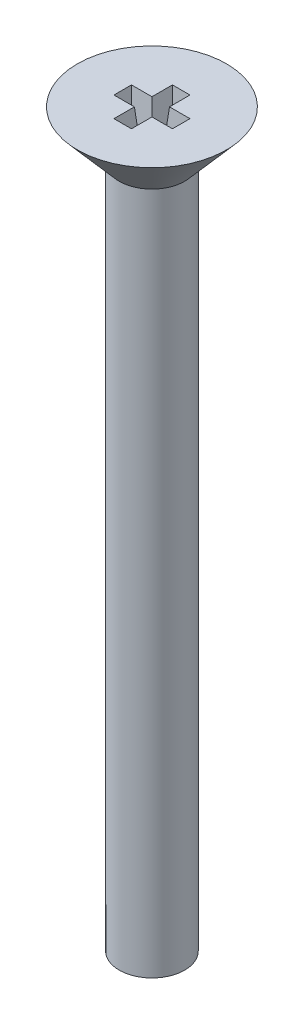
SolidWorks part; units mm, degrees
ref_plane "Front Plane" through (0, 0, 0) normal (0, 0, 1) x (1, 0, 0)
ref_plane "Top Plane" through (0, 0, 0) normal (0, 1, 0) x (1, 0, 0)
ref_plane "Right Plane" through (0, 0, 0) normal (1, 0, 0) x (0, 0, -1)
sketch "Sketch1" plane through (0, 0, 0) normal (0, 0, 1) x (1, 0, 0)
  line L1 (1.4224, 0) -> (3.2385, 2.0892)
  line L5 (3.2385, 2.0892) -> (0, 2.0892)
  line L6 (0, 2.0892) -> (0, 0)
  line L7 (0, 0) -> (0, -29.6608)
  line L8 (0, -29.6608) -> (1.4224, -29.6608)
  line L9 (1.4224, -29.6608) -> (1.4224, 0)
  line L11 (1.4224, 0) -> (0, 0) construction
  dimension "D1" = 31.75
  dimension "D2" = 1.4224
  dimension "D3" = 41
  dimension "D4" = 3.2385
revolve "Revolve1" add sketch "Sketch1" angle 360 about L7
sketch "Sketch2" plane through (0, 2.0892, 0) normal (0, 1, 0) x (1, 0, 0)
  line L0 (-0.381, 1.27) -> (0.381, 1.27)
  line L1 (0.381, 1.27) -> (0.381, 0.381)
  line L2 (0.381, 0.381) -> (1.27, 0.381)
  line L3 (1.27, 0.381) -> (1.27, -0.381)
  line L4 (1.27, -0.381) -> (0.381, -0.381)
  line L5 (0.381, -0.381) -> (0.381, -1.27)
  line L6 (0.381, -1.27) -> (-0.381, -1.27)
  line L7 (-0.381, -1.27) -> (-0.381, -0.381)
  line L8 (-0.381, -0.381) -> (-1.27, -0.381)
  line L9 (-1.27, -0.381) -> (-1.27, 0.381)
  line L10 (-1.27, 0.381) -> (-0.381, 0.381)
  line L11 (-0.381, 0.381) -> (-0.381, 1.27)
  line L12 (0, 1.27) -> (0, 0) construction
  line L13 (0, 0) -> (0, -1.27) construction
  line L14 (1.27, 0) -> (0, 0) construction
  line L15 (-1.27, 0) -> (0, 0) construction
  dimension "D1" = 0.762
  dimension "D2" = 1.27
extrude "Cut-Extrude1" cut sketch "Sketch2" against normal blind 2.159 draft 5
